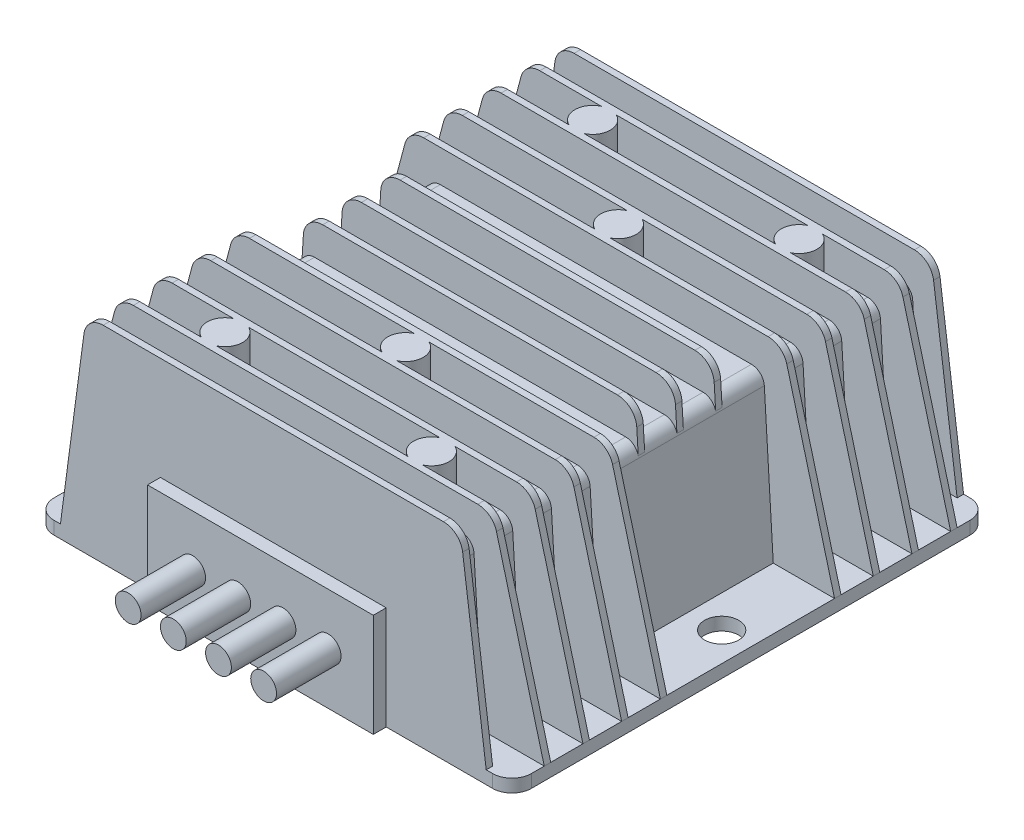
SolidWorks part; units mm, degrees
material "6061 合金"
ref_plane "前视基准面" through (0, 0, 0) normal (0, 0, 1) x (1, 0, 0)
ref_plane "上视基准面" through (0, 0, 0) normal (0, 1, 0) x (1, 0, 0)
ref_plane "右视基准面" through (0, 0, 0) normal (1, 0, 0) x (0, 0, -1)
sketch "草图1" plane through (0, 0, 0) normal (0, 1, 0) x (1, 0, 0)
  line L1 (-34, -37) -> (34, -37)
  line L2 (-37, -34) -> (-37, 34)
  line L3 (-34, 37) -> (34, 37)
  line L4 (37, -34) -> (37, 34)
  line L5 (-37, -37) -> (37, 37) construction
  line L6 (-37, 37) -> (37, -37) construction
  arc A0 (-34, -37) -> (-37, -34) centre (-34, -34) cw
  arc A1 (34, -37) -> (37, -34) centre (34, -34) ccw
  arc A2 (34, 37) -> (37, 34) centre (34, 34) cw
  arc A3 (-37, 34) -> (-34, 37) centre (-34, 34) cw
  point P0 (0, 0)
  dimension "D2" = 3
  dimension "D1" = 74
extrude "凸台-拉伸1" add sketch "草图1" along normal blind 2
sketch "草图2" plane through (0, 2, 0) normal (0, 1, 0) x (1, 0, 0)
  line L1 (-27.5, -37) -> (27.5, -37)
  line L2 (-27.5, -37) -> (-27.5, 37)
  line L3 (-27.5, 37) -> (27.5, 37)
  line L4 (27.5, -37) -> (27.5, 37)
  line L5 (-27.5, -37) -> (27.5, 37) construction
  line L6 (-27.5, 37) -> (27.5, -37) construction
  line L7 (34, 37) -> (-34, 37) construction
  point P0 (0, 0)
  dimension "D1" = 74
  dimension "D2" = 55
extrude "凸台-拉伸2" add sketch "草图2" along normal blind 25
sketch "草图3" plane through (0, 0, 37) normal (0, 0, 1) x (1, 0, 0)
  line L0 (-27.5, 2) -> (-27.5, 27)
  line L1 (-27.5, 27) -> (-26, 27)
  line L2 (-27.5, 27) -> (27.5, 27) construction
  line L3 (-26, 27) -> (-27.5, 2)
  line L4 (0, 0) -> (0, 27) construction
  line L5 (27.5, 27) -> (26, 27)
  line L6 (27.5, 2) -> (27.5, 27)
  line L7 (26, 27) -> (27.5, 2)
  dimension "D1" = 1.5
extrude "切除-拉伸1" cut sketch "草图3" against normal up to next
fillet "圆角1" radius 2 2 edges at (26, 27, 0) (-26, 27, 0)
sketch "草图4" plane through (0, 0, 37) normal (0, 0, 1) x (1, 0, 0)
  line L0 (-33, 2) -> (-29.3471, 29.3965)
  line L1 (-34, 2) -> (-27.5, 2) construction
  line L2 (-26.3735, 32) -> (26.3735, 32)
  line L3 (29.3471, 29.3965) -> (33, 2)
  line L4 (27.5, 2) -> (34, 2) construction
  line L5 (33, 2) -> (-33, 2)
  line L6 (-34, 0) -> (34, 0) construction
  arc A0 (26.3735, 32) -> (29.3471, 29.3965) centre (26.3735, 29) cw
  arc A1 (-29.3471, 29.3965) -> (-26.3735, 32) centre (-26.3735, 29) cw
  point P10 (0, 2)
  point P15 (29, 32)
  point P18 (-29, 32)
  dimension "D4" = 3
  dimension "D1" = 32
  dimension "D2" = 33
  dimension "D3" = 58
extrude "凸台-拉伸3" add sketch "草图4" against normal blind 1
sketch "草图5" plane through (0, 0, 37) normal (0, 0, 1) x (1, 0, 0)
  line L0 (-37, 2) -> (-29.5939, 29.773)
  line L1 (-26.6952, 32) -> (26.6952, 32)
  line L2 (29.5939, 29.773) -> (37, 2)
  line L3 (37, 2) -> (-37, 2)
  arc A0 (26.6952, 32) -> (29.5939, 29.773) centre (26.6952, 29) cw
  arc A1 (-29.5939, 29.773) -> (-26.6952, 32) centre (-26.6952, 29) cw
  point P8 (0, 32)
  point P12 (29, 32)
  point P15 (-29, 32)
  dimension "D3" = 3
  dimension "D1" = 30
  dimension "D2" = 58
extrude "凸台-拉伸4" add sketch "草图5" along normal blind 1 from offset 6 offset against normal yes
pattern_linear "阵列(线性)1" count 4 spacing 6 along (0, 0, -1) of "凸台-拉伸4"
mirror "镜向1" about plane through (0, 0, 0) normal (0, 0, 1) of "凸台-拉伸3", "阵列(线性)1", "凸台-拉伸4"
sketch "草图6" plane through (0, 0, 0) normal (0, 0, 1) x (1, 0, 0)
  line L0 (-27.5, 2) -> (-25.8395, 29.1829)
  line L1 (26.6952, 32) -> (-26.6952, 32) construction
  line L2 (-22.845, 32) -> (22.845, 32)
  line L3 (25.8395, 29.1829) -> (27.5, 2)
  line L4 (27.5, 2) -> (37, 2) construction
  line L5 (27.5, 2) -> (-27.5, 2)
  arc A0 (22.845, 32) -> (25.8395, 29.1829) centre (22.845, 29) cw
  arc A1 (-25.8395, 29.1829) -> (-22.845, 32) centre (-22.845, 29) cw
  point P10 (0, 32)
  point P14 (25.6674, 32)
  point P17 (-25.6674, 32)
  dimension "D2" = 3
  dimension "D1" = 51.3348
extrude "凸台-拉伸5" add sketch "草图6" along normal mid plane 1
pattern_linear "阵列(线性)2" count 2 spacing 6 along (0, 0, 1) of "凸台-拉伸5"
pattern_linear "阵列(线性)3" count 2 spacing 6 along (0, 0, -1) of "凸台-拉伸5"
hole_wizard "M5 间隙孔1" positions "草图7" profile "草图8" hole size "M5" standard "GB" end condition up to next
sketch "草图7" plane through (0, 2, 0) normal (0, 1, 0) x (1, 0, 0)
  point P0 (-32.5, 0)
  point P2 (32.5, 0)
  dimension "D1" = 65
  dimension "D2" = 32.5
sketch "草图8" plane through (-32.5, 2, 0) normal (1, 0, 0) x (0, 0, 1)
  line L0 (0, 0) -> (0, 2)
  line L1 (0, 2) -> (2.65, 2)
  line L2 (2.65, 2) -> (2.65, 0)
  line L5 (2.65, 0) -> (0, 0)
  line L11 (0, -6.35) -> (0, 107.95) construction
  dimension "通孔孔直径" = 5.3
  dimension "通孔孔深度" = 2
sketch "草图9" plane through (0, 27, 0) normal (0, 1, 0) x (1, 0, 0)
  line L2 (-37, 0) -> (37, 0) construction
  line L3 (-37, 13) -> (-37, -13) construction
  line L4 (37, -13) -> (37, 13) construction
  line L5 (24.1164, 31) -> (-24.1164, 31) construction
  line L6 (26.6952, 19) -> (-26.6952, 19) construction
  circle A0 centre (-16, 28.5) radius 2.75
  circle A1 centre (16, 28.5) radius 2.75
  circle A2 centre (0, 16.5) radius 2.75
  circle A3 centre (16, -28.5) radius 2.75
  circle A4 centre (0, -16.5) radius 2.75
  circle A5 centre (-16, -28.5) radius 2.75
  dimension "D1" = 5.5
  dimension "D2" = 5.5
  dimension "D3" = 5.5
  dimension "D4" = 32
  dimension "D5" = 16
  dimension "D6" = 2.5
  dimension "D7" = 2.5
extrude "凸台-拉伸9" add sketch "草图9" along normal up to surface (5 mm away) up to face at (0, 32, 0)
sketch "草图10" plane through (0, 0, 37) normal (0, 0, 1) x (1, 0, 0)
  line L0 (-34, 0) -> (34, 0) construction
  line L1 (-17.5, 0) -> (17.5, 0)
  line L2 (-17.5, 0) -> (-17.5, 16)
  line L3 (-17.5, 16) -> (17.5, 16)
  line L4 (17.5, 0) -> (17.5, 16)
  line L5 (-17.5, 0) -> (17.5, 16) construction
  line L6 (-17.5, 16) -> (17.5, 0) construction
  point P4 (0, 8)
  dimension "D1" = 16
  dimension "D2" = 35
extrude "凸台-拉伸10" add sketch "草图10" along normal blind 2
sketch "草图11" plane through (0, 0, 39) normal (0, 0, 1) x (1, 0, 0)
  line L0 (-17.5, 16) -> (-17.5, 0) construction
  circle A0 centre (-10.5, 8) radius 2
  circle A1 centre (-3.5, 8) radius 2
  circle A2 centre (3.5, 8) radius 2
  circle A3 centre (10.5, 8) radius 2
  point P4 (-17.5, 8)
  dimension "D1" = 4
  dimension "D2" = 10.5
  dimension "D4" = 7
  dimension "D3" = 4
extrude "凸台-拉伸11" add sketch "草图11" along normal blind 10
